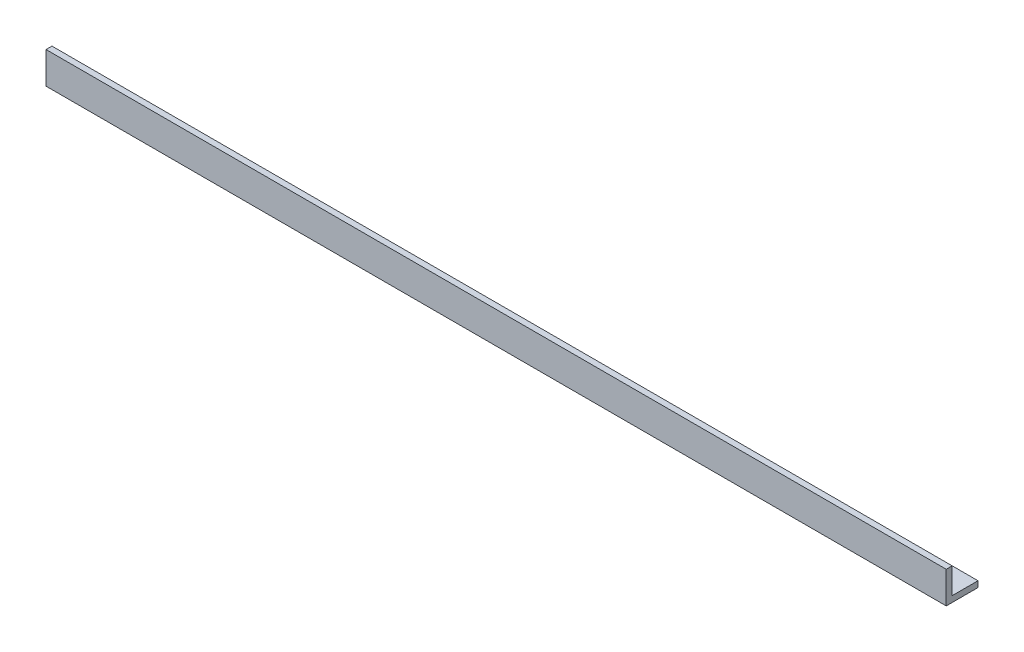
SolidWorks part; units mm, degrees
ref_plane "Front Plane" through (0, 0, 0) normal (0, 0, 1) x (1, 0, 0)
ref_plane "Top Plane" through (0, 0, 0) normal (0, 1, 0) x (1, 0, 0)
ref_plane "Right Plane" through (0, 0, 0) normal (1, 0, 0) x (0, 0, -1)
sketch "Sketch1" plane through (0, 0, 0) normal (1, 0, 0) x (0, 0, -1)
  line L0 (0, 0) -> (0, -20.6375)
  line L1 (0, -20.6375) -> (20.6375, -20.6375)
  line L2 (-4.7625, 0) -> (-4.7625, -25.4)
  line L3 (-4.7625, -25.4) -> (20.6375, -25.4)
  line L4 (0, 0) -> (-4.7625, 0)
  line L5 (20.6375, -20.6375) -> (20.6375, -25.4)
  dimension "D2" = 25.4
  dimension "D3" = 25.4
  dimension "D1" = 4.7625
extrude "Boss-Extrude1" add sketch "Sketch1" along normal blind 720.09
sketch "Sketch3" plane through (0, -20.6375, 0) normal (0, 1, 0) x (1, 0, 0)
  line L0 (0, 20.6375) -> (0, 0) construction
  line L1 (720.09, 20.6375) -> (0, 20.6375) construction
  circle A0 centre (38.1, 7.9375) radius 3.175
  dimension "D1" = 6.35
  dimension "D2" = 38.1
  dimension "D3" = 12.7
extrude "Cut-Extrude1" cut sketch "Sketch3" against normal up to next
